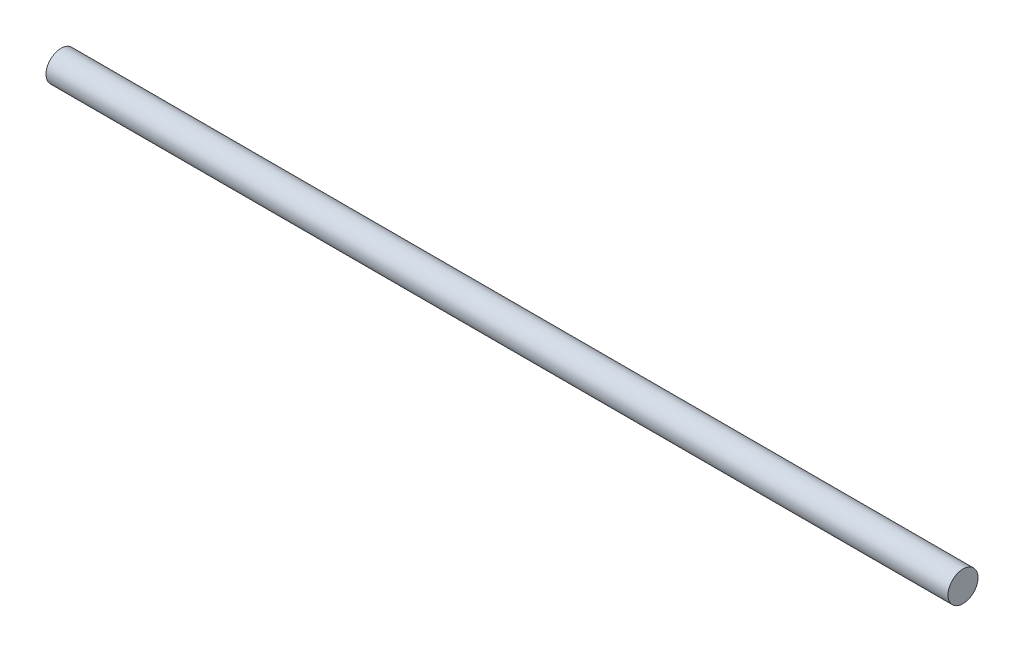
SolidWorks part; units mm, degrees
ref_plane "Front Plane" through (0, 0, 0) normal (0, 0, 1) x (1, 0, 0)
ref_plane "Top Plane" through (0, 0, 0) normal (0, 1, 0) x (1, 0, 0)
ref_plane "Right Plane" through (0, 0, 0) normal (1, 0, 0) x (0, 0, -1)
sketch "Sketch1" plane through (0, 0, 0) normal (0, 0, 1) x (1, 0, 0)
  line L0 (0, 0) -> (32.7516, 0)
sketch "Sketch2" plane through (0, 0, 0) normal (1, 0, 0) x (0, 0, -1)
  circle A0 centre (0, 0) radius 1.5
  dimension "D1" = 3
extrude "Boss-Extrude1" add sketch "Sketch2" along normal blind 90
